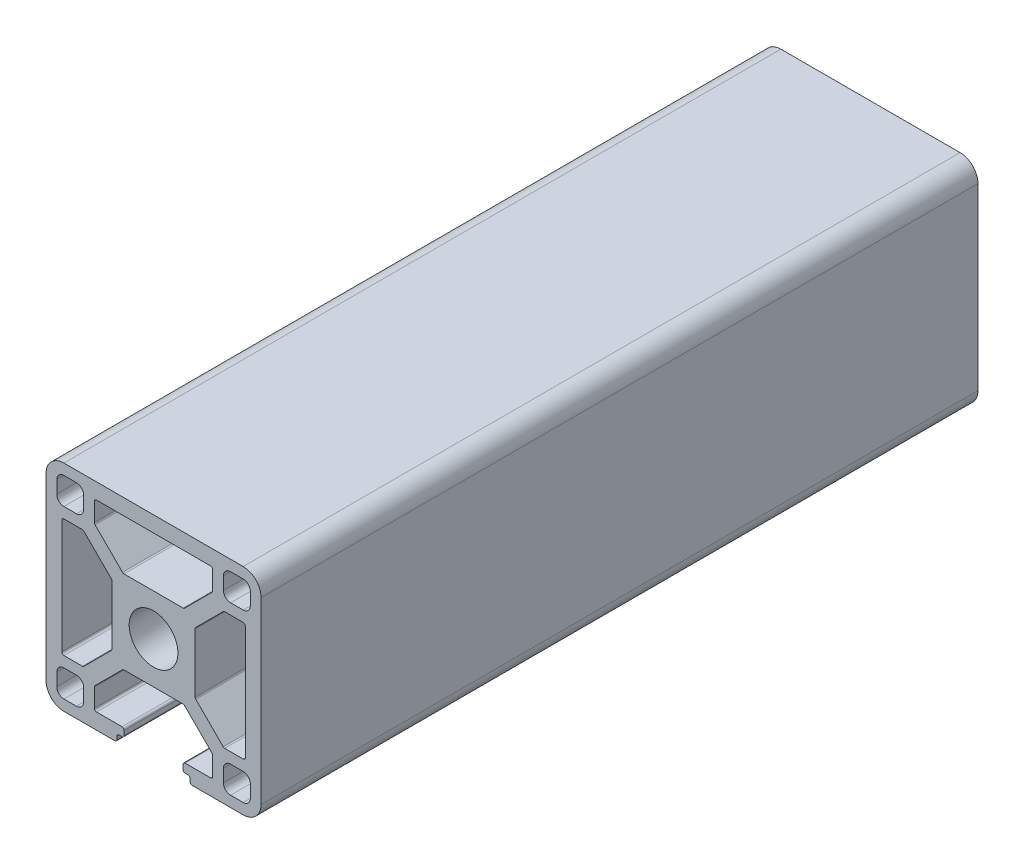
SolidWorks part; units mm, degrees
ref_plane "前视基准面" through (0, 0, 0) normal (0, 0, 1) x (1, 0, 0)
ref_plane "上视基准面" through (0, 0, 0) normal (0, 1, 0) x (1, 0, 0)
ref_plane "右视基准面" through (0, 0, 0) normal (1, 0, 0) x (0, 0, -1)
sketch "草图1" plane through (0, 0, 0) normal (0, 0, 1) x (1, 0, 0)
  line B0 (12.5, 15) -> (-12.5, 15)
  line B1 (-15, 12.5) -> (-15, -12.5)
  line B2 (-12.5, -15) -> (-5.4, -15)
  line B3 (-5.1, -14.7) -> (-5.1, -14.3)
  line B4 (-4.8, -14) -> (-4.4, -14)
  line B5 (-4.1, -13.7) -> (-4.1, -13.1)
  line B6 (-4.4, -12.8) -> (-7.95, -12.8)
  line B7 (-8.25, -12.5) -> (-8.25, -9.9299)
  line B8 (-8.1621, -9.7178) -> (-4.3322, -5.8879)
  line B9 (-4.1201, -5.8) -> (4.1201, -5.8)
  line B10 (4.3322, -5.8879) -> (8.1621, -9.7178)
  line B11 (8.25, -9.9299) -> (8.25, -12.5)
  line B12 (7.95, -12.8) -> (4.4, -12.8)
  line B13 (4.1, -13.1) -> (4.1, -13.7)
  line B14 (4.4, -14) -> (4.8, -14)
  line B15 (5.1, -14.3) -> (5.1, -14.7)
  line B16 (5.4, -15) -> (12.5, -15)
  line B17 (15, -12.5) -> (15, 12.5)
  line B18 (7.95, 12.8) -> (-7.95, 12.8)
  line B19 (-8.25, 12.5) -> (-8.25, 9.9299)
  line B20 (-8.1621, 9.7178) -> (-4.3322, 5.8879)
  line B21 (-4.1201, 5.8) -> (4.1201, 5.8)
  line B22 (4.3322, 5.8879) -> (8.1621, 9.7178)
  line B23 (8.25, 9.9299) -> (8.25, 12.5)
  line B24 (10.75, 9.75) -> (12.5, 9.75)
  line B25 (13.5, 10.75) -> (13.5, 12.5)
  line B26 (12.5, 13.5) -> (10.75, 13.5)
  line B27 (9.75, 12.5) -> (9.75, 10.75)
  line B28 (-13.5, 12.5) -> (-13.5, 10.75)
  line B29 (-12.5, 9.75) -> (-10.75, 9.75)
  line B30 (-9.75, 10.75) -> (-9.75, 12.5)
  line B31 (-10.75, 13.5) -> (-12.5, 13.5)
  line B32 (9.75, -10.75) -> (9.75, -12.5)
  line B33 (10.75, -13.5) -> (12.5, -13.5)
  line B34 (13.5, -12.5) -> (13.5, -10.75)
  line B35 (12.5, -9.75) -> (10.75, -9.75)
  line B36 (-5.8, -4.1201) -> (-5.8, 4.1201)
  line B37 (-5.8879, 4.3322) -> (-9.7178, 8.1621)
  line B38 (-9.9299, 8.25) -> (-12.5, 8.25)
  line B39 (-12.8, 7.95) -> (-12.8, -7.95)
  line B40 (-12.5, -8.25) -> (-9.9299, -8.25)
  line B41 (-9.7178, -8.1621) -> (-5.8879, -4.3322)
  line B42 (5.8, 4.1201) -> (5.8, -4.1201)
  line B43 (5.8879, -4.3322) -> (9.7178, -8.1621)
  line B44 (9.9299, -8.25) -> (12.5, -8.25)
  line B45 (12.8, -7.95) -> (12.8, 7.95)
  line B46 (12.5, 8.25) -> (9.9299, 8.25)
  line B47 (9.7178, 8.1621) -> (5.8879, 4.3322)
  line B48 (-10.75, -9.75) -> (-12.5, -9.75)
  line B49 (-13.5, -10.75) -> (-13.5, -12.5)
  line B50 (-12.5, -13.5) -> (-10.75, -13.5)
  line B51 (-9.75, -12.5) -> (-9.75, -10.75)
  arc B52 (-12.5, 15) -> (-15, 12.5) centre (-12.5, 12.5) ccw
  arc B53 (-15, -12.5) -> (-12.5, -15) centre (-12.5, -12.5) ccw
  arc B54 (-5.4, -15) -> (-5.1, -14.7) centre (-5.4, -14.7) ccw
  arc B55 (-4.8, -14) -> (-5.1, -14.3) centre (-4.8, -14.3) ccw
  arc B56 (-4.4, -14) -> (-4.1, -13.7) centre (-4.4, -13.7) ccw
  arc B57 (-4.1, -13.1) -> (-4.4, -12.8) centre (-4.4, -13.1) ccw
  arc B58 (-8.25, -12.5) -> (-7.95, -12.8) centre (-7.95, -12.5) ccw
  arc B59 (-8.1621, -9.7178) -> (-8.25, -9.9299) centre (-7.95, -9.9299) ccw
  arc B60 (-4.1201, -5.8) -> (-4.3322, -5.8879) centre (-4.1201, -6.1) ccw
  arc B61 (4.3322, -5.8879) -> (4.1201, -5.8) centre (4.1201, -6.1) ccw
  arc B62 (8.25, -9.9299) -> (8.1621, -9.7178) centre (7.95, -9.9299) ccw
  arc B63 (7.95, -12.8) -> (8.25, -12.5) centre (7.95, -12.5) ccw
  arc B64 (4.4, -12.8) -> (4.1, -13.1) centre (4.4, -13.1) ccw
  arc B65 (4.1, -13.7) -> (4.4, -14) centre (4.4, -13.7) ccw
  arc B66 (5.1, -14.3) -> (4.8, -14) centre (4.8, -14.3) ccw
  arc B67 (5.1, -14.7) -> (5.4, -15) centre (5.4, -14.7) ccw
  arc B68 (12.5, -15) -> (15, -12.5) centre (12.5, -12.5) ccw
  arc B69 (15, 12.5) -> (12.5, 15) centre (12.5, 12.5) ccw
  arc B70 (-7.95, 12.8) -> (-8.25, 12.5) centre (-7.95, 12.5) ccw
  arc B71 (-8.25, 9.9299) -> (-8.1621, 9.7178) centre (-7.95, 9.9299) ccw
  arc B72 (-4.3322, 5.8879) -> (-4.1201, 5.8) centre (-4.1201, 6.1) ccw
  arc B73 (4.1201, 5.8) -> (4.3322, 5.8879) centre (4.1201, 6.1) ccw
  arc B74 (8.1621, 9.7178) -> (8.25, 9.9299) centre (7.95, 9.9299) ccw
  arc B75 (8.25, 12.5) -> (7.95, 12.8) centre (7.95, 12.5) ccw
  arc B76 (9.75, 10.75) -> (10.75, 9.75) centre (10.75, 10.75) ccw
  arc B77 (12.5, 9.75) -> (13.5, 10.75) centre (12.5, 10.75) ccw
  arc B78 (13.5, 12.5) -> (12.5, 13.5) centre (12.5, 12.5) ccw
  arc B79 (10.75, 13.5) -> (9.75, 12.5) centre (10.75, 12.5) ccw
  arc B80 (-13.5, 10.75) -> (-12.5, 9.75) centre (-12.5, 10.75) ccw
  arc B81 (-10.75, 9.75) -> (-9.75, 10.75) centre (-10.75, 10.75) ccw
  arc B82 (-9.75, 12.5) -> (-10.75, 13.5) centre (-10.75, 12.5) ccw
  arc B83 (-12.5, 13.5) -> (-13.5, 12.5) centre (-12.5, 12.5) ccw
  arc B84 (10.75, -9.75) -> (9.75, -10.75) centre (10.75, -10.75) ccw
  arc B85 (9.75, -12.5) -> (10.75, -13.5) centre (10.75, -12.5) ccw
  arc B86 (12.5, -13.5) -> (13.5, -12.5) centre (12.5, -12.5) ccw
  arc B87 (13.5, -10.75) -> (12.5, -9.75) centre (12.5, -10.75) ccw
  arc B88 (-5.8879, -4.3322) -> (-5.8, -4.1201) centre (-6.1, -4.1201) ccw
  arc B89 (-5.8, 4.1201) -> (-5.8879, 4.3322) centre (-6.1, 4.1201) ccw
  arc B90 (-9.7178, 8.1621) -> (-9.9299, 8.25) centre (-9.9299, 7.95) ccw
  arc B91 (-12.5, 8.25) -> (-12.8, 7.95) centre (-12.5, 7.95) ccw
  arc B92 (-12.8, -7.95) -> (-12.5, -8.25) centre (-12.5, -7.95) ccw
  arc B93 (-9.9299, -8.25) -> (-9.7178, -8.1621) centre (-9.9299, -7.95) ccw
  arc B94 (5.8879, 4.3322) -> (5.8, 4.1201) centre (6.1, 4.1201) ccw
  arc B95 (5.8, -4.1201) -> (5.8879, -4.3322) centre (6.1, -4.1201) ccw
  arc B96 (9.7178, -8.1621) -> (9.9299, -8.25) centre (9.9299, -7.95) ccw
  arc B97 (12.5, -8.25) -> (12.8, -7.95) centre (12.5, -7.95) ccw
  arc B98 (12.8, 7.95) -> (12.5, 8.25) centre (12.5, 7.95) ccw
  arc B99 (9.9299, 8.25) -> (9.7178, 8.1621) centre (9.9299, 7.95) ccw
  arc B100 (-9.75, -10.75) -> (-10.75, -9.75) centre (-10.75, -10.75) ccw
  arc B101 (-12.5, -9.75) -> (-13.5, -10.75) centre (-12.5, -10.75) ccw
  arc B102 (-13.5, -12.5) -> (-12.5, -13.5) centre (-12.5, -12.5) ccw
  arc B103 (-10.75, -13.5) -> (-9.75, -12.5) centre (-10.75, -12.5) ccw
  circle B104 centre (0, 0) radius 3.4
sketch_block_instance "A$C544953CF-1"
sketch_block "A$C544953CF"
extrude "凸台-拉伸1" add sketch "草图1" along normal mid plane 100
